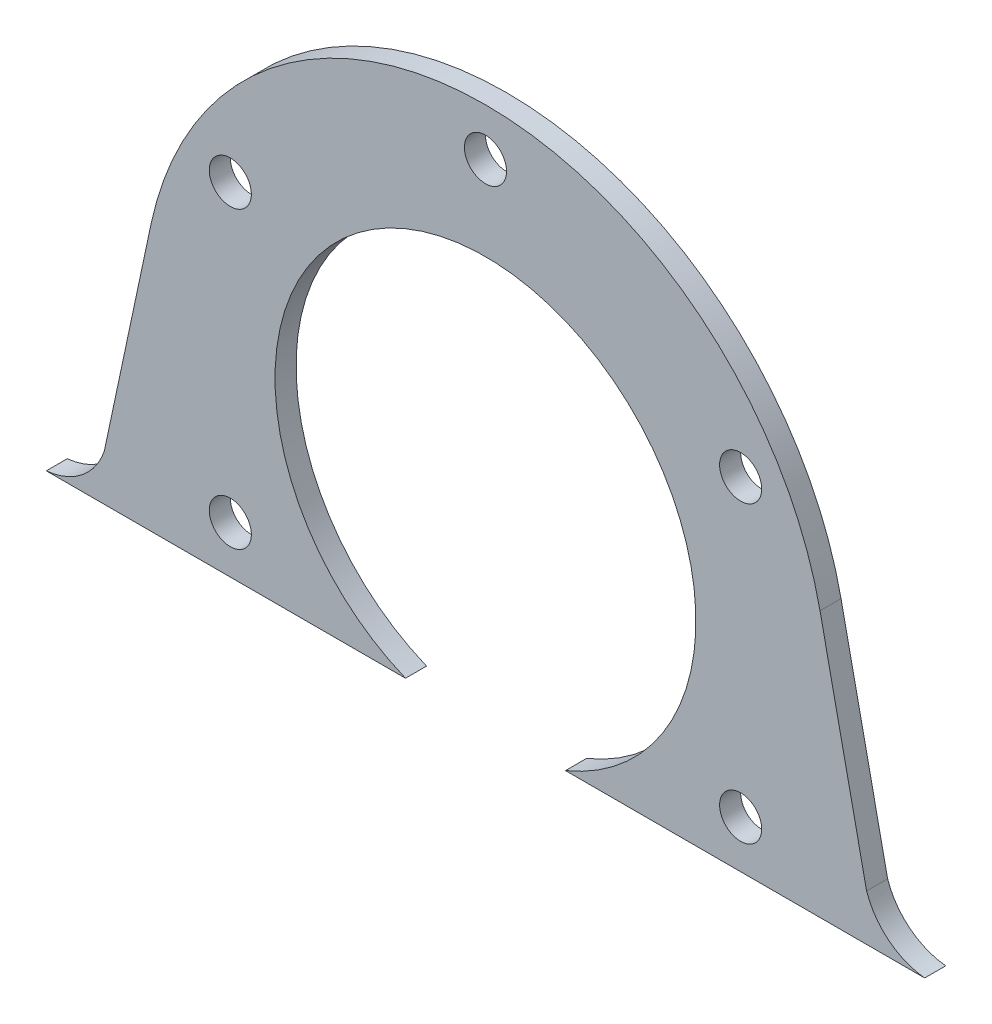
SolidWorks part; units mm, degrees
ref_plane "Front Plane" through (0, 0, 0) normal (0, 0, 1) x (1, 0, 0)
ref_plane "Top Plane" through (0, 0, 0) normal (0, 1, 0) x (1, 0, 0)
ref_plane "Right Plane" through (0, 0, 0) normal (1, 0, 0) x (0, 0, -1)
sketch "Sketch1" plane through (0, 0, 0) normal (0, 0, 1) x (1, 0, 0)
  line L3 (-50, -79) -> (50, -79)
  line L4 (0, 0) -> (0, -28) construction
  line L6 (-50, -79) -> (-31.7912, 6.7507)
  line L7 (50, -79) -> (31.7912, 6.7507)
  line L9 (0, -28) -> (-70.4492, -28) construction
  line L10 (0, -69) -> (0, -97.2613) construction
  arc A0 (31.7912, 6.7507) -> (-31.7912, 6.7507) centre (0, 0) ccw
  circle A1 centre (0, 0) radius 20
  circle A2 centre (0, 28) radius 2
  circle A3 centre (24.2487, 14) radius 2
  circle A4 centre (24.2487, -14) radius 2
  circle A6 centre (-24.2487, -14) radius 2
  circle A7 centre (-24.2487, 14) radius 2
  circle A8 centre (0, -28) radius 2 [skipped]
  circle A9 centre (0, -71.5) radius 2.5
  circle A10 centre (23, -46.5) radius 2.5
  circle A11 centre (-23, -46.5) radius 2.5
  point P19 (0, 0)
  dimension "D1" = 40
  dimension "D2" = 65
  dimension "D5" = 4
  dimension "D10" = 5
  dimension "D11" = 5
  dimension "D12" = 5
  dimension "D3" = 28
  dimension "D6" = 25
  dimension "D7" = 100
  dimension "D8" = 51
  dimension "D9" = 23
  dimension "D13" = 50
  dimension "D14" = 7.5
  dimension "D15" = 28
  dimension "D16" = 23
  dimension "D4" = 6
extrude "Boss-Extrude1" add sketch "Sketch1" along normal blind 2
sketch "Sketch2" plane through (0, 0, 0) normal (0, 0, -1) x (-1, 0, 0)
  line L1 (-50, -79) -> (50.063, -79)
  line L2 (-50, -79) -> (-50, -18.5)
  line L3 (-50, -18.5) -> (50.063, -18.5)
  line L4 (50.063, -79) -> (50.063, -18.5)
  arc A0 (31.7912, 6.7507) -> (-31.7912, 6.7507) centre (0, 0) ccw construction
  point P8 (0, 32.5)
  point P9 (0.0315, -18.5)
  dimension "D1" = 51
extrude "Cut-Extrude1" cut sketch "Sketch2" against normal blind 10
sketch "Sketch3" plane through (0, 0, 2) normal (0, 0, 1) x (1, 0, 0)
  line L1 (-31.7912, 6.7507) -> (-37.1531, -18.5) construction
  line L2 (-36.2188, -14.1002) -> (-37.1531, -18.5)
  line L3 (-36.2188, -14.1002) -> (-37.1531, -18.5)
  line L4 (-36.2188, -14.1002) -> (-37.1531, -18.5)
  line L6 (-41.7392, -18.5) -> (-37.1531, -18.5)
  arc A0 (-36.2188, -14.1002) -> (-41.7392, -18.5) centre (-42.3651, -12.0516) cw
  point P1 (-36.2188, -13.9021)
extrude "Boss-Extrude2" add sketch "Sketch3" against normal blind 2 contours L2 A0 L6
mirror "Mirror1" about plane through (0, 0, 0) normal (1, 0, 0) of "Boss-Extrude2"
